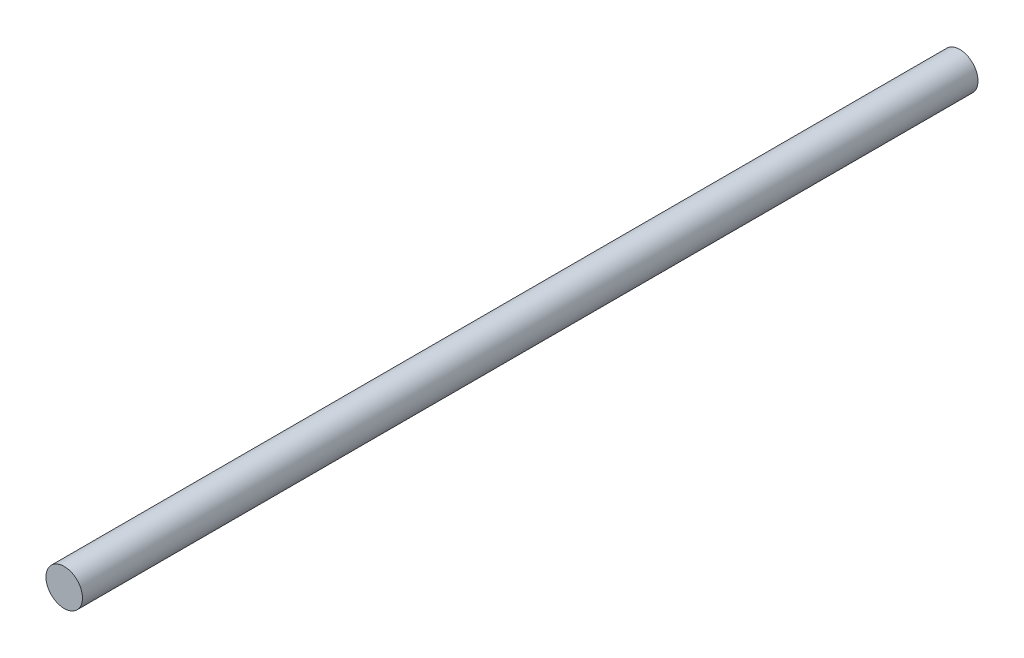
SolidWorks part; units mm, degrees
ref_plane "Front Plane" through (0, 0, 0) normal (0, 0, 1) x (1, 0, 0)
ref_plane "Top Plane" through (0, 0, 0) normal (0, 1, 0) x (1, 0, 0)
ref_plane "Right Plane" through (0, 0, 0) normal (1, 0, 0) x (0, 0, -1)
sketch "Sketch2" plane through (0, 0, 0) normal (0, 0, 1) x (1, 0, 0)
  circle A0 centre (0, 0) radius 0.815
  dimension "D1" = 1.63
extrude "Boss-Extrude2" add sketch "Sketch2" along normal blind 40
